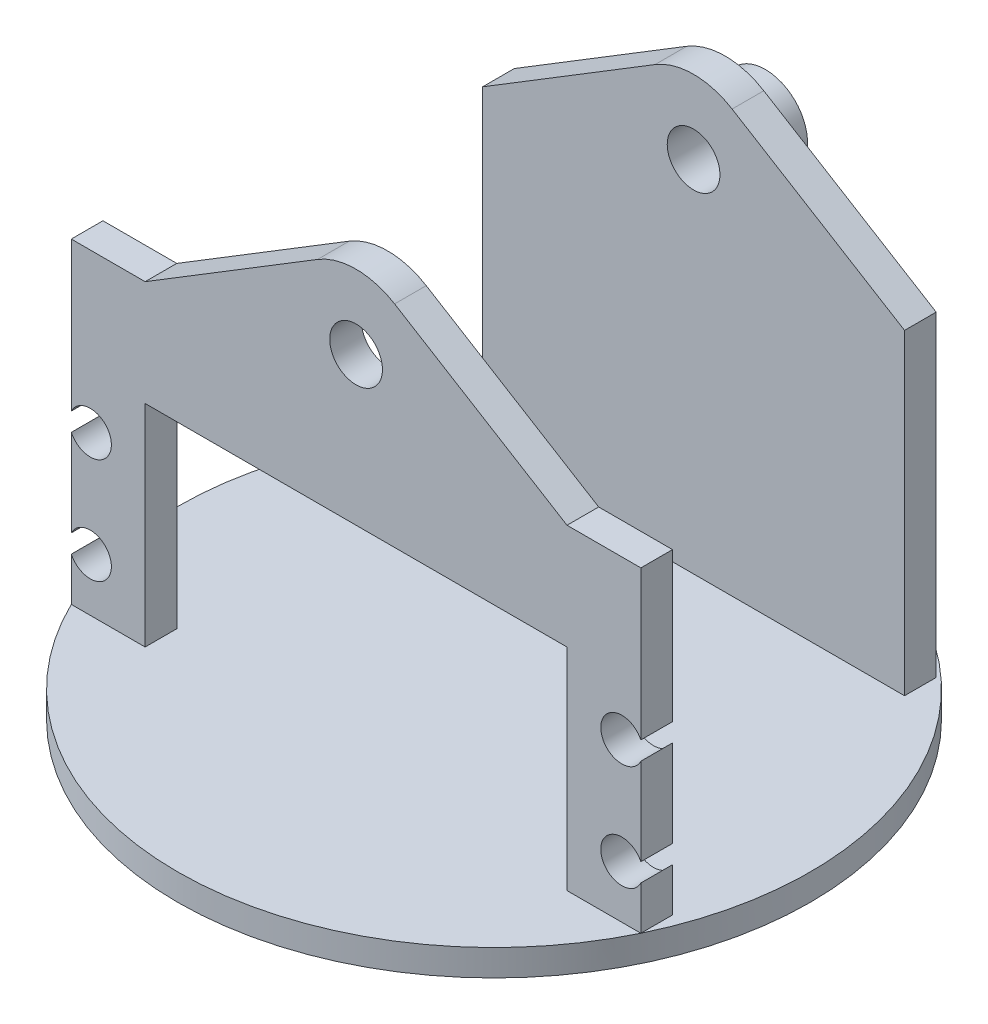
SolidWorks part; units mm, degrees
material "PE Alta densidad"
ref_plane "Alzado" through (0, 0, 0) normal (0, 0, 1) x (1, 0, 0)
ref_plane "Planta" through (0, 0, 0) normal (0, 1, 0) x (1, 0, 0)
ref_plane "Vista lateral" through (0, 0, 0) normal (1, 0, 0) x (0, 0, -1)
sketch "Croquis1" plane through (0, 0, 0) normal (0, 0, 1) x (1, 0, 0)
  line L0 (0, 5.2693) -> (0, -5.2693) construction
  line L7 (0, 0) -> (0, 2)
  line L8 (0, 2) -> (-30, 2)
  line L9 (-30, 2) -> (-30, -0.5)
  line L10 (-30, -0.5) -> (-5.5, -0.5)
  line L11 (-5.5, -0.5) -> (-5.5, -2.75)
  line L12 (-5.5, -2.75) -> (-2.9, -2.75)
  line L13 (-2.9, -2.75) -> (-2.9, 0)
  line L14 (-2.9, 0) -> (0, 0)
  point P3 (0, 0)
  dimension "D1" = 2.25
  dimension "D2" = 2.6
  dimension "D3" = 2.9
  dimension "D4" = 30
  dimension "D5" = 2.75
  dimension "D6" = 2
revolve "Revolución1" add sketch "Croquis1" angle 360 about L0
sketch "Croquis2" plane through (0, 2, 0) normal (0, 1, 0) x (1, 0, 0)
  line L0 (27, -13.0767) -> (-27, -13.0767)
  line L1 (27, -10.0767) -> (-27, -10.0767)
  line L2 (-27, -13.0767) -> (-27, -10.0767)
  line L3 (27, -13.0767) -> (27, -10.0767)
  circle A1 centre (0, 0) radius 30
  circle A2 centre (0, 0) radius 30
  dimension "D2" = 54
  dimension "D1" = 0
  dimension "D3" = 3
extrude "Saliente-Extruir1" add sketch "Croquis2" along normal blind 30 contours L0 L3 L1 L2
sketch "Croquis3" plane through (0, 0, 13.0767) normal (0, 0, 1) x (1, 0, 0)
  line L0 (27, 2) -> (-27, 2) construction
  line L1 (20, 22) -> (-20, 22)
  line L2 (20, 22) -> (20, 2)
  line L3 (20, 2) -> (-20, 2)
  line L4 (-20, 22) -> (-20, 2)
  line L5 (-20, 12) -> (-20, 2) construction
extrude "Cortar-Extruir1" cut sketch "Croquis3" against normal up to next
sketch "Croquis4" plane through (0, 0, 13.0767) normal (0, 0, 1) x (1, 0, 0)
  line L10 (20, 22) -> (20, 2)
  line L11 (20, 2) -> (27, 2)
  line L12 (27, 2) -> (27, 32)
  line L13 (27, 32) -> (-27, 32)
  line L14 (-27, 32) -> (-27, 2)
  line L15 (-27, 2) -> (-20, 2)
  line L16 (-20, 2) -> (-20, 22)
  line L17 (-20, 22) -> (20, 22)
  line L18 (20, 22) -> (20, 2)
  line L19 (20, 2) -> (27, 2)
  line L20 (27, 2) -> (27, 32)
  line L21 (27, 32) -> (-27, 32)
  line L22 (-27, 32) -> (-27, 2)
  line L23 (-27, 2) -> (-20, 2)
  line L24 (-20, 2) -> (-20, 22)
  line L25 (-20, 22) -> (20, 22)
  circle A1 centre (-25.2, 17) radius 2
  circle A2 centre (-25.2, 7) radius 2
  dimension "D5" = 4
  dimension "D1" = 25.2
  dimension "D2" = 0
  dimension "D3" = 10
  dimension "D4" = 5
extrude "Cortar-Extruir2" cut sketch "Croquis4" against normal blind 10 contours L22 A1 | L22 A2
mirror "Simetría1" about plane through (0, 0, 0) normal (1, 0, 0) of "Cortar-Extruir2"
sketch "Croquis5" plane through (0, 0, 13.0767) normal (0, 0, 1) x (1, 0, 0)
  line L0 (-20, 32) -> (-3.6528, 42)
  line L1 (27, 32) -> (-27, 32) construction
  line L2 (-20, 32) -> (20, 32)
  line L3 (3.6528, 42) -> (20, 32)
  line L4 (0, 53.9129) -> (0, -7.9085) construction
  arc A0 (3.6528, 42) -> (-3.6528, 42) centre (0, 36.0287) ccw
  circle A1 centre (0, 36.0287) radius 2.5
  dimension "D1" = 7
  dimension "D4" = 5
  dimension "D2" = 10
  dimension "D3" = 20
extrude "Saliente-Extruir2" add sketch "Croquis5" against normal blind 3
ref_plane "Plano1" through (0, 0, -18.9233) normal (0, 0, -1) x (-1, 0, 0)
sketch "Croquis6" plane through (0, 0, -18.9233) normal (0, 0, -1) x (-1, 0, 0)
  line L0 (-20, 2) -> (-20, 32)
  line L1 (-20, 32) -> (-3.6528, 42)
  line L3 (3.6528, 42) -> (20, 32)
  line L4 (20, 32) -> (20, 2)
  line L5 (20, 2) -> (-20, 2)
  circle A0 centre (0, 36.0287) radius 2.5 construction
  circle A1 centre (0, 36.0287) radius 2.5
  arc A2 (3.6528, 42) -> (-3.6528, 42) centre (0, 36.0287) ccw construction
  arc A3 (3.6528, 42) -> (-3.6528, 42) centre (0, 36.0287) ccw
extrude "Saliente-Extruir3" add sketch "Croquis6" along normal blind 3
sketch "Croquis7" plane through (0, 0, -21.9233) normal (0, 0, -1) x (-1, 0, 0)
  circle A0 centre (0, 36.0287) radius 2.5 construction
  circle A3 centre (0, 36.0287) radius 2.5
  circle A4 centre (0, 36.0287) radius 4
  dimension "D1" = 8
extrude "Saliente-Extruir4" add sketch "Croquis7" along normal blind 1.8
sketch "Croquis8" plane through (0, 0, -23.7233) normal (0, 0, -1) x (-1, 0, 0)
  circle A1 centre (0, 36.0287) radius 4
  circle A2 centre (0, 36.0287) radius 4
  dimension "D1" = 0
extrude "Saliente-Extruir5" add sketch "Croquis8" along normal blind 2
